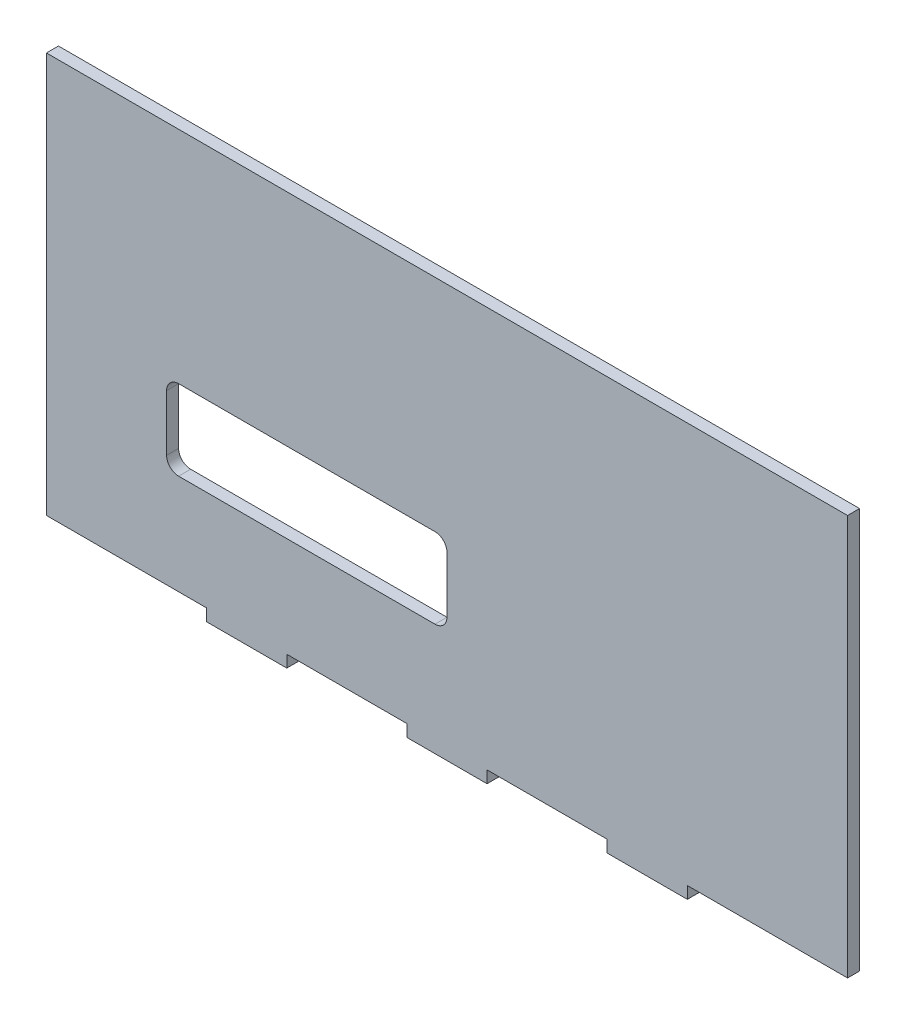
SolidWorks part; units mm, degrees
ref_plane "Front Plane" through (0, 0, 0) normal (0, 0, 1) x (1, 0, 0)
ref_plane "Top Plane" through (0, 0, 0) normal (0, 1, 0) x (1, 0, 0)
ref_plane "Right Plane" through (0, 0, 0) normal (1, 0, 0) x (0, 0, -1)
sketch "Sketch1" plane through (0, 0, 0) normal (0, 0, 1) x (1, 0, 0)
  line L0 (-100, -50) -> (-60, -50) construction
  line L1 (-100, -50) -> (-60, -50)
  line L2 (-100, -50) -> (-100, 50)
  line L3 (-100, 50) -> (100, 50)
  line L4 (100, -50) -> (100, 50)
  line L5 (-100, -50) -> (100, 50) construction
  line L6 (-100, 50) -> (100, -50) construction
  line L7 (-40, -50) -> (-10, -50) construction
  line L8 (10, -50) -> (40, -50) construction
  line L9 (60, -50) -> (100, -50) construction
  line L10 (-40, -50) -> (-10, -50)
  line L11 (-60, -53) -> (-40, -53)
  line L12 (-60, -53) -> (-60, -50)
  line L14 (-40, -53) -> (-40, -50)
  line L15 (-100, -50) -> (-100, -25) construction
  line L16 (-100, -25) -> (-70, -25) construction
  line L17 (-10, -53) -> (10, -53)
  line L18 (-10, -53) -> (-10, -50)
  line L20 (10, -53) -> (10, -50)
  line L22 (-67, -25) -> (-3, -25)
  line L23 (40, -53) -> (60, -53)
  line L24 (40, -53) -> (40, -50)
  line L26 (60, -53) -> (60, -50)
  line L27 (-70, -22) -> (-70, -8)
  line L28 (-67, -5) -> (-3, -5)
  line L29 (10, -50) -> (40, -50)
  line L30 (60, -50) -> (100, -50)
  line L31 (0, -22) -> (0, -8)
  arc A0 (-70, -8) -> (-67, -5) centre (-67, -8) cw
  arc A1 (-3, -5) -> (0, -8) centre (-3, -8) cw
  arc A2 (-3, -25) -> (0, -22) centre (-3, -22) ccw
  arc A3 (-70, -22) -> (-67, -25) centre (-67, -22) ccw
  point P0 (0, 0)
  point P17 (-70, -5)
  point P28 (0, -5)
  dimension "D12" = 3
  dimension "D13" = 3
  dimension "D14" = 3
  dimension "D15" = 3
  dimension "D1" = 100
  dimension "D2" = 200
  dimension "D3" = 20
  dimension "D4" = 20
  dimension "D5" = 20
  dimension "D6" = 3
  dimension "D7" = 3
  dimension "D8" = 3
  dimension "D9" = 70
  dimension "D10" = 20
  dimension "D11" = 25
extrude "Boss-Extrude1" add sketch "Sketch1" along normal blind 3
